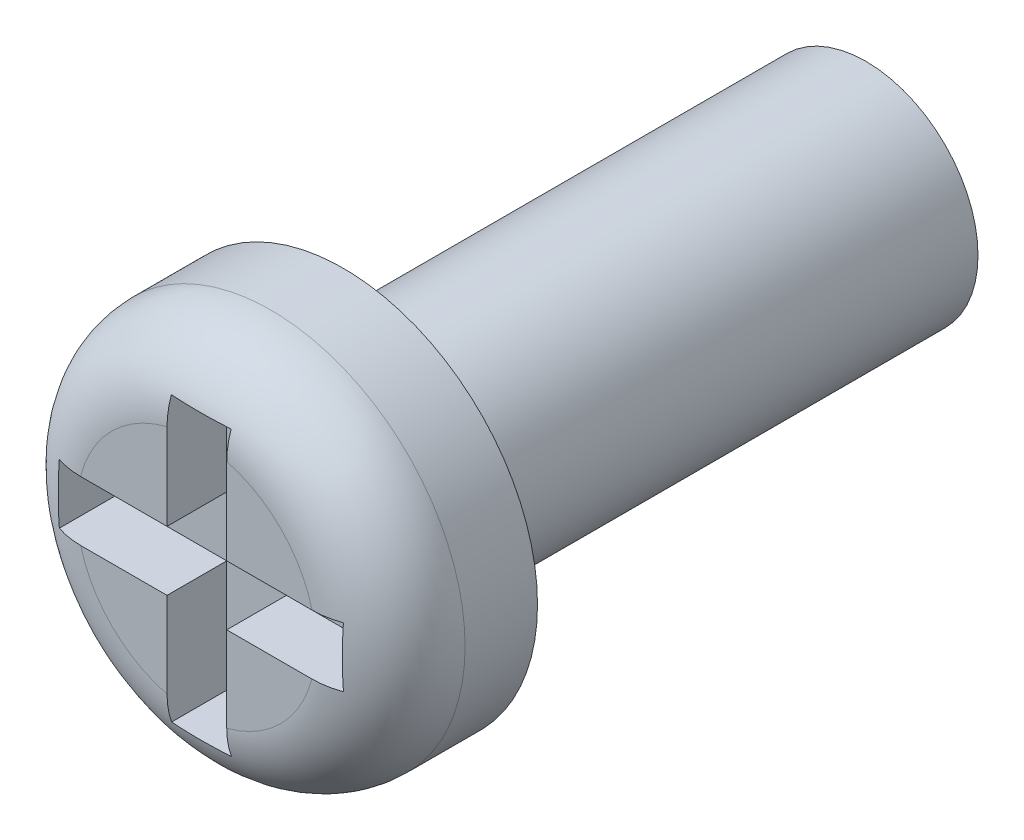
SolidWorks part; units mm, degrees
ref_plane "Front Plane" through (0, 0, 0) normal (0, 0, 1) x (1, 0, 0)
ref_plane "Top Plane" through (0, 0, 0) normal (0, 1, 0) x (1, 0, 0)
ref_plane "Right Plane" through (0, 0, 0) normal (1, 0, 0) x (0, 0, -1)
sketch "Sketch1" plane through (0, 0, 0) normal (0, 0, 1) x (1, 0, 0)
  circle A0 centre (0, 0) radius 2.6
  dimension "D1" = 5.2
extrude "Boss-Extrude1" add sketch "Sketch1" along normal blind 1.97
sketch "Sketch2" plane through (0, 0, 0) normal (0, 0, -1) x (-1, 0, 0)
  circle A0 centre (0, 0) radius 1.5
  dimension "D1" = 3
extrude "Boss-Extrude2" add sketch "Sketch2" along normal blind 7
fillet "Fillet1" radius 1 1 edges at (2.6, 0, 1.97)
sketch "Sketch3" plane through (0, 0, 1.97) normal (0, 0, 1) x (1, 0, 0)
  line L0 (-0.3923, 0.3947) -> (-0.3923, 1.8947)
  line L1 (-0.3923, 1.8947) -> (0.4077, 1.8947)
  line L2 (0.4077, 1.8947) -> (0.4077, 0.3947)
  line L3 (0.4077, 0.3947) -> (1.9077, 0.3947)
  line L4 (1.9077, 0.3947) -> (1.9077, -0.4053)
  line L5 (1.9077, -0.4053) -> (0.4077, -0.4053)
  line L6 (0.4077, -0.4053) -> (0.4077, -1.9053)
  line L7 (0.4077, -1.9053) -> (-0.3923, -1.9053)
  line L8 (-0.3923, -1.9053) -> (-0.3923, -0.4053)
  line L9 (-0.3923, -0.4053) -> (-1.8923, -0.4053)
  line L10 (-1.8923, -0.4053) -> (-1.8923, 0.3947)
  line L11 (-1.8923, 0.3947) -> (-0.3923, 0.3947)
  circle A1 centre (0, 0) radius 2.6 construction
  dimension "D12" = 0.4053
  dimension "D1" = 0.8
  dimension "D2" = 1.5
  dimension "D3" = 0.8
  dimension "D4" = 0.8
  dimension "D5" = 0.8
  dimension "D6" = 1.5
  dimension "D7" = 1.5
  dimension "D8" = 1.5
  dimension "D9" = 1.5
  dimension "D10" = 1.5
  dimension "D11" = 0.4077
extrude "Cut-Extrude1" cut sketch "Sketch3" against normal blind 0.8
